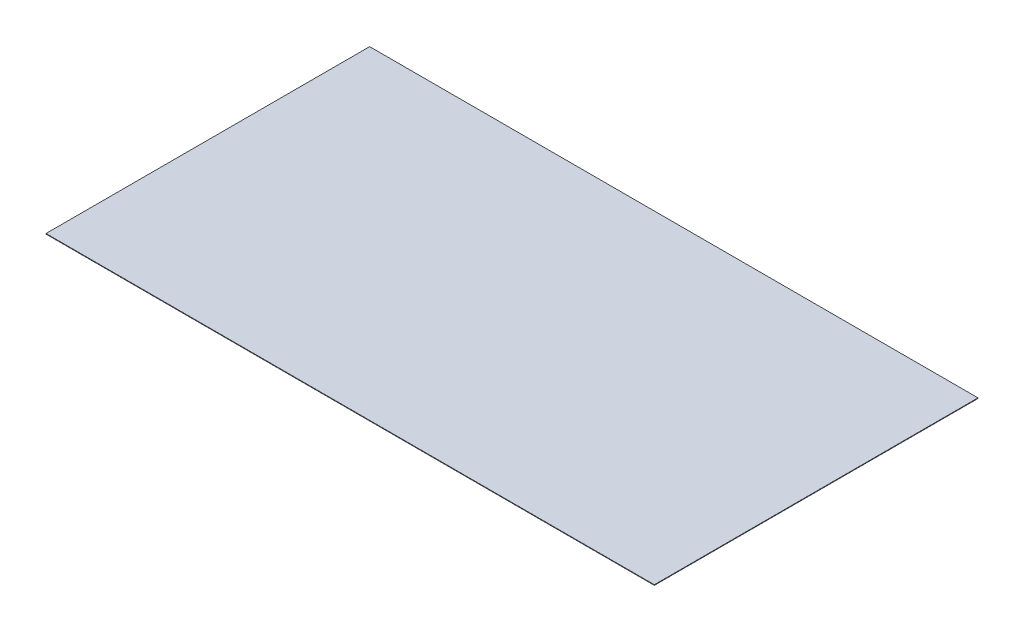
SolidWorks part; units mm, degrees
ref_plane "Alzado" through (0, 0, 0) normal (0, 0, 1) x (1, 0, 0)
ref_plane "Planta" through (0, 0, 0) normal (0, 1, 0) x (1, 0, 0)
ref_plane "Vista lateral" through (0, 0, 0) normal (1, 0, 0) x (0, 0, -1)
sketch "Croquis1" plane through (0, 0, 0) normal (0, 1, 0) x (1, 0, 0)
  line L1 (1094, -582) -> (-1094, -582)
  line L2 (1094, -582) -> (1094, 582)
  line L3 (1094, 582) -> (-1094, 582)
  line L4 (-1094, -582) -> (-1094, 582)
  line L5 (1094, -582) -> (-1094, 582) construction
  line L6 (1094, 582) -> (-1094, -582) construction
  point P0 (0, 0)
  dimension "D1" = 2188
  dimension "D2" = 1164
extrude "Extruir1" add sketch "Croquis1" along normal blind 2
